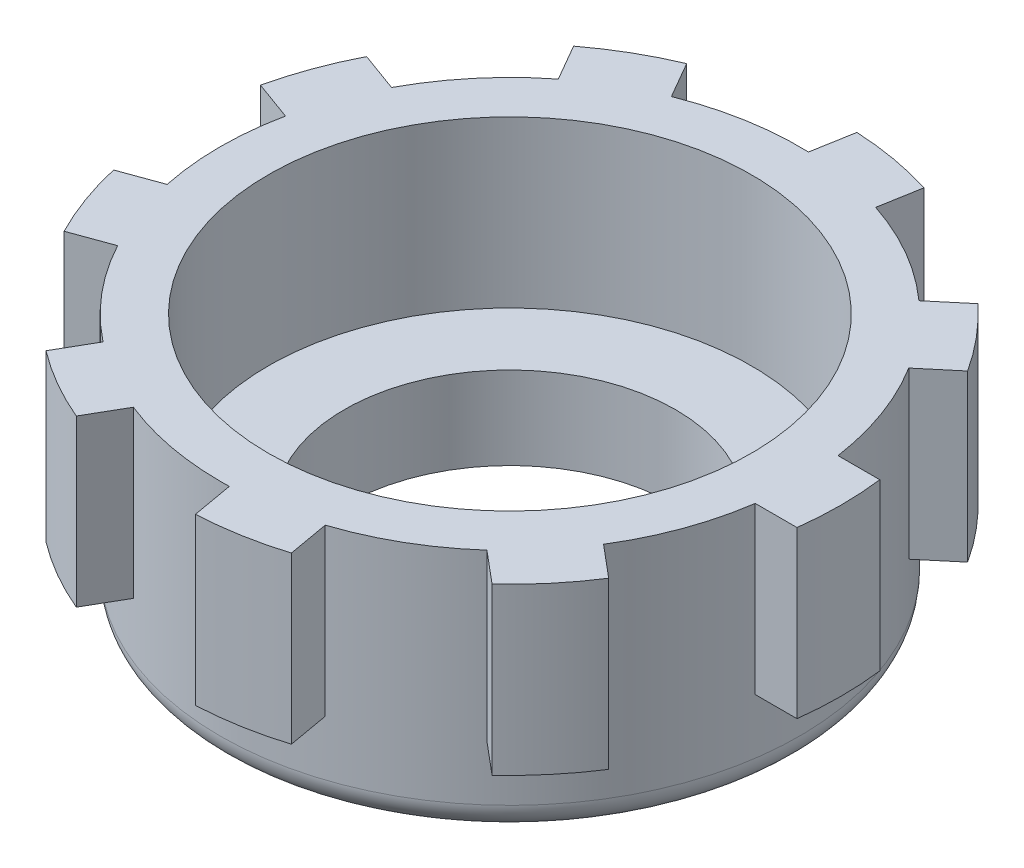
SolidWorks part; units mm, degrees
ref_plane "Front Plane" through (0, 0, 0) normal (0, 0, 1) x (1, 0, 0)
ref_plane "Top Plane" through (0, 0, 0) normal (0, 1, 0) x (1, 0, 0)
ref_plane "Right Plane" through (0, 0, 0) normal (1, 0, 0) x (0, 0, -1)
sketch "Sketch1" plane through (0, 0, 0) normal (0, 1, 0) x (1, 0, 0)
  circle A0 centre (0, 0) radius 24
  dimension "D1" = 48
extrude "Boss-Extrude1" add sketch "Sketch1" along normal blind 18
hole_wizard "Hole2" positions "Sketch4" profile "Sketch5" legacy end condition up to next
sketch "Sketch4" plane through (0, 18, 0) normal (0, 1, 0) x (1, 0, 0)
  point P0 (0, 0)
sketch "Sketch5" plane through (0, 18, 0) normal (1, 0, 0) x (0, 0, 1)
  line L0 (0, 0) -> (0, 25.2103)
  line L1 (0, 25.2103) -> (12, 18)
  line L2 (12, 18) -> (12, 12)
  line L3 (12, 12) -> (17.5, 12)
  line L4 (17.5, 0) -> (0, 0)
  line L5 (0, -11.3109) -> (0, 121.1557) construction
  line L6 (0, 25.2103) -> (-12, 18) construction
  line L7 (17.5, 12) -> (17.5, 0)
  dimension "Depth" = 18
  dimension "Drill Angle" = 118
  dimension "Diameter" = 24
  dimension "C-Bore Diameter" = 35
  dimension "C-Bore Depth" = 12
sketch "Sketch6" plane through (0, 18, 0) normal (0, 1, 0) x (1, 0, 0)
  line L0 (0, 0) -> (39.295, 0) construction
  line L1 (20.7846, 3) -> (23.8118, 3)
  line L2 (20.7846, -3) -> (23.8118, -3)
  line L3 (17.8503, -11.062) -> (20.1692, -13.0078)
  line L4 (13.9936, -15.6582) -> (16.3125, -17.604)
  line L5 (6.5636, -19.9479) -> (7.0893, -22.9291)
  line L6 (0.6548, -20.9898) -> (1.1804, -23.971)
  line L7 (-7.7942, -19.5) -> (-9.3078, -22.1216)
  line L8 (-12.9904, -16.5) -> (-14.504, -19.1216)
  line L9 (-18.5051, -9.9278) -> (-21.3497, -10.9632)
  line L10 (-20.5572, -4.2897) -> (-23.4018, -5.325)
  line L11 (-20.5572, 4.2897) -> (-23.4018, 5.325)
  line L12 (-18.5051, 9.9278) -> (-21.3497, 10.9632)
  line L13 (-12.9904, 16.5) -> (-14.504, 19.1216)
  line L14 (-7.7942, 19.5) -> (-9.3078, 22.1216)
  line L15 (0.6548, 20.9898) -> (1.1804, 23.971)
  line L16 (6.5636, 19.9479) -> (7.0893, 22.9291)
  line L17 (13.9936, 15.6582) -> (16.3125, 17.604)
  line L18 (17.8503, 11.062) -> (20.1692, 13.0078)
  circle A0 centre (0, 0) radius 24 construction
  arc A1 (-23.4018, 5.325) -> (-23.4018, -5.325) centre (0, 0) ccw
  arc A2 (-20.5572, 4.2897) -> (-20.5572, -4.2897) centre (0, 0) ccw
  arc A3 (-14.504, 19.1216) -> (-21.3497, 10.9632) centre (0, 0) ccw
  arc A4 (-12.9904, 16.5) -> (-18.5051, 9.9278) centre (0, 0) ccw
  arc A5 (0.6548, 20.9898) -> (-7.7942, 19.5) centre (0, 0) ccw
  arc A6 (1.1804, 23.971) -> (-9.3078, 22.1216) centre (0, 0) ccw
  arc A7 (13.9936, 15.6582) -> (6.5636, 19.9479) centre (0, 0) ccw
  arc A8 (16.3125, 17.604) -> (7.0893, 22.9291) centre (0, 0) ccw
  arc A9 (20.7846, 3) -> (17.8503, 11.062) centre (0, 0) ccw
  arc A10 (23.8118, 3) -> (20.1692, 13.0078) centre (0, 0) ccw
  arc A11 (17.8503, -11.062) -> (20.7846, -3) centre (0, 0) ccw
  arc A12 (20.1692, -13.0078) -> (23.8118, -3) centre (0, 0) ccw
  arc A13 (7.0893, -22.9291) -> (16.3125, -17.604) centre (0, 0) ccw
  arc A14 (6.5636, -19.9479) -> (13.9936, -15.6582) centre (0, 0) ccw
  arc A15 (-7.7942, -19.5) -> (0.6548, -20.9898) centre (0, 0) ccw
  arc A16 (-9.3078, -22.1216) -> (1.1804, -23.971) centre (0, 0) ccw
  arc A17 (-18.5051, -9.9278) -> (-12.9904, -16.5) centre (0, 0) ccw
  arc A18 (-21.3497, -10.9632) -> (-14.504, -19.1216) centre (0, 0) ccw
  point P8 (0, 0)
  point P44 (0, 0)
  dimension "D1" = 42
  dimension "D2" = 6
  dimension "D3" = 9
extrude "Cut-Extrude1" cut sketch "Sketch6" against normal blind 12
sketch "Sketch7" plane through (0, 0, 0) normal (0, -1, 0) x (1, 0, 0)
  circle A0 centre (0, 0) radius 24 construction
  circle A1 centre (0, 0) radius 24
  circle A2 centre (0, 0) radius 21
  dimension "D1" = 42
extrude "Cut-Extrude2" cut sketch "Sketch7" against normal blind 6
fillet "Fillet1" radius 2 1 edges at (0, 0, -21)
